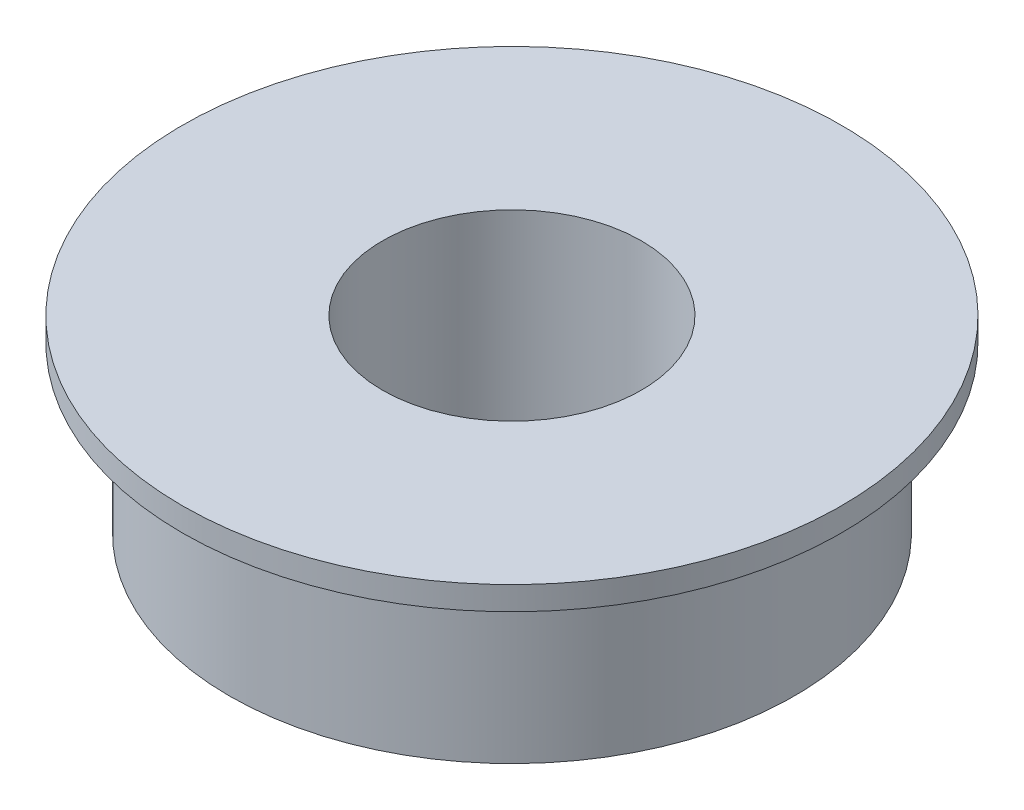
SolidWorks part; units mm, degrees
ref_plane "Front Plane" through (0, 0, 0) normal (0, 0, 1) x (1, 0, 0)
ref_plane "Top Plane" through (0, 0, 0) normal (0, 1, 0) x (1, 0, 0)
ref_plane "Right Plane" through (0, 0, 0) normal (1, 0, 0) x (0, 0, -1)
sketch "Sketch1" plane through (0, 0, 0) normal (0, 1, 0) x (1, 0, 0)
  circle A0 centre (0, 0) radius 2.75
  circle A1 centre (0, 0) radius 6
  dimension "D1" = 5.5
  dimension "D2" = 12
extrude "Boss-Extrude1" add sketch "Sketch1" along normal blind 4
sketch "Sketch2" plane through (0, 4, 0) normal (0, 1, 0) x (1, 0, 0)
  circle A0 centre (0, 0) radius 7
  circle A1 centre (0, 0) radius 6 construction
  circle A2 centre (0, 0) radius 2.75 construction
  circle A3 centre (0, 0) radius 2.75
  dimension "D1" = 1
extrude "Boss-Extrude2" add sketch "Sketch2" against normal blind 0.5
